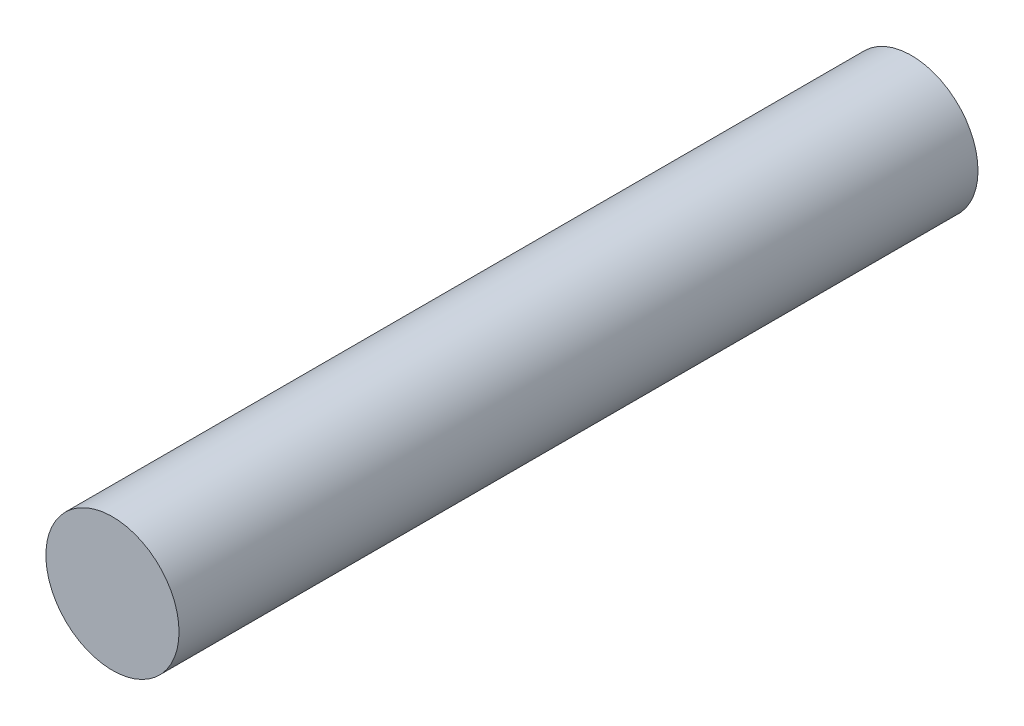
SolidWorks part; units mm, degrees
ref_plane "Front Plane" through (0, 0, 0) normal (0, 0, 1) x (1, 0, 0)
ref_plane "Top Plane" through (0, 0, 0) normal (0, 1, 0) x (1, 0, 0)
ref_plane "Right Plane" through (0, 0, 0) normal (1, 0, 0) x (0, 0, -1)
sketch "Sketch1" plane through (0, 0, 0) normal (0, 0, 1) x (1, 0, 0)
  circle A0 centre (0, 0) radius 2.25
  dimension "D1" = 4.5
extrude "Boss-Extrude1" add sketch "Sketch1" along normal blind 27
